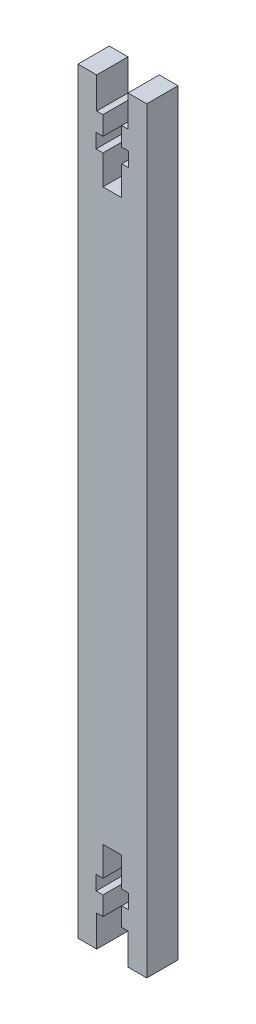
SolidWorks part; units mm, degrees
ref_plane "Front Plane" through (0, 0, 0) normal (0, 0, 1) x (1, 0, 0)
ref_plane "Top Plane" through (0, 0, 0) normal (0, 1, 0) x (1, 0, 0)
ref_plane "Right Plane" through (0, 0, 0) normal (1, 0, 0) x (0, 0, -1)
sketch "Sketch1" plane through (0, 0, 0) normal (0, 0, 1) x (1, 0, 0)
  line L0 (-9, 116) -> (-9, 5)
  line L5 (-20, 116) -> (-20, 5)
  line L6 (-14.5, 5) -> (-14.5, 16.2208) construction
  line L7 (-16, 5) -> (-17, 5)
  line L8 (-17, 0) -> (-20, 0)
  line L9 (-20, 0) -> (-20, 5)
  line L10 (-17, 0) -> (-17, 5)
  line L11 (-13, 5) -> (-12, 5)
  line L12 (-12, 5) -> (-12, 0)
  line L13 (-12, 0) -> (-9, 0)
  line L14 (-9, 0) -> (-9, 5)
  line L15 (-14.5, 116) -> (-14.5, 94.1792) construction
  line L16 (-13, 116) -> (-12, 116)
  line L17 (-12, 121) -> (-9, 121)
  line L18 (-9, 121) -> (-9, 116)
  line L19 (-12, 121) -> (-12, 116)
  line L20 (-16, 116) -> (-17, 116)
  line L21 (-17, 116) -> (-17, 121)
  line L22 (-17, 121) -> (-20, 121)
  line L23 (-20, 121) -> (-20, 116)
  line L24 (-13, 116) -> (-16, 116) construction
  line L25 (-16, 116) -> (-16, 113)
  line L26 (-16, 110.7) -> (-17.1, 110.7)
  line L27 (-11.9, 113) -> (-11.9, 110.7)
  line L28 (-17.1, 113) -> (-16, 113)
  line L29 (-16, 110.7) -> (-16, 106)
  line L30 (-16, 106) -> (-13, 106)
  line L31 (-13, 106) -> (-13, 110.7)
  line L32 (-13, 113) -> (-11.9, 113)
  line L33 (-17.1, 110.7) -> (-17.1, 113)
  line L34 (-11.9, 110.7) -> (-13, 110.7)
  line L35 (-13, 113) -> (-13, 116)
  line L36 (-14.5, 106) -> (-14.5, 116) construction
  line L37 (-16, 5) -> (-13, 5) construction
  line L38 (-13, 5) -> (-13, 8)
  line L39 (-13, 10.3) -> (-11.9, 10.3)
  line L40 (-17.1, 8) -> (-17.1, 10.3)
  line L41 (-11.9, 8) -> (-13, 8)
  line L42 (-13, 10.3) -> (-13, 15)
  line L43 (-13, 15) -> (-16, 15)
  line L44 (-16, 15) -> (-16, 10.3)
  line L45 (-16, 8) -> (-17.1, 8)
  line L46 (-11.9, 10.3) -> (-11.9, 8)
  line L47 (-17.1, 10.3) -> (-16, 10.3)
  line L48 (-16, 8) -> (-16, 5)
  line L49 (-14.5, 15) -> (-14.5, 5) construction
  point P4 (-18.5, 0)
  dimension "D1" = 5
  dimension "D2" = 3
  dimension "D3" = 5
  dimension "D5" = 3
  dimension "D6" = 5
  dimension "D7" = 5.2
  dimension "D8" = 3
  dimension "D9" = 2.3
  dimension "D10" = 3
  dimension "D11" = 10
  dimension "D12" = 5.2
  dimension "D13" = 3
  dimension "D14" = 2.3
  dimension "D15" = 3
  dimension "D16" = 10
  dimension "D17" = 121
extrude "Boss-Extrude1" add sketch "Sketch1" along normal blind 5
sketch "Sketch2" plane through (0, 0, 5) normal (0, 0, 1) x (1, 0, 0)
  line L0 (-18.9476, 274.152) -> (-18.9476, -26.6804) construction
  line L1 (-9, 0) -> (-9, 121) construction
  dimension "D1" = 9.9476
